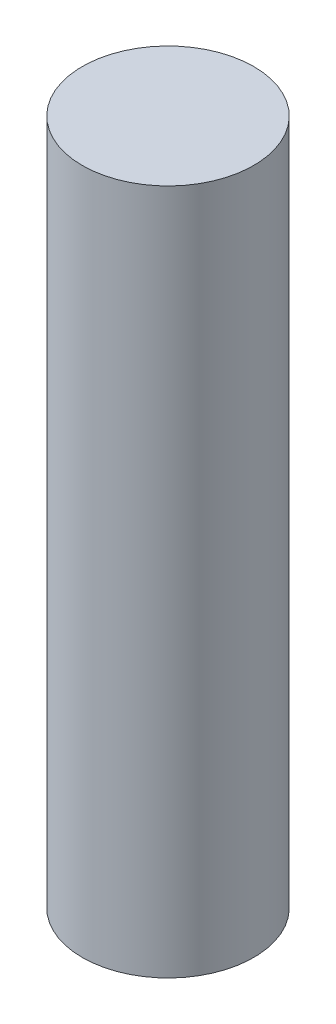
SolidWorks part; units mm, degrees
ref_plane "Plan de face" through (0, 0, 0) normal (0, 0, 1) x (1, 0, 0)
ref_plane "Plan de dessus" through (0, 0, 0) normal (0, 1, 0) x (1, 0, 0)
ref_plane "Plan de droite" through (0, 0, 0) normal (1, 0, 0) x (0, 0, -1)
sketch "Esquisse1" plane through (0, 0, 0) normal (0, 1, 0) x (1, 0, 0)
  circle A0 centre (0, 0) radius 3
  dimension "D1" = 6
extrude "Boss.-Extru.1" add sketch "Esquisse1" along normal mid plane 24
sketch "Esquisse2" plane through (0, 0, 0) normal (0, 1, 0) x (1, 0, 0)
  point P0 (0, 0)
